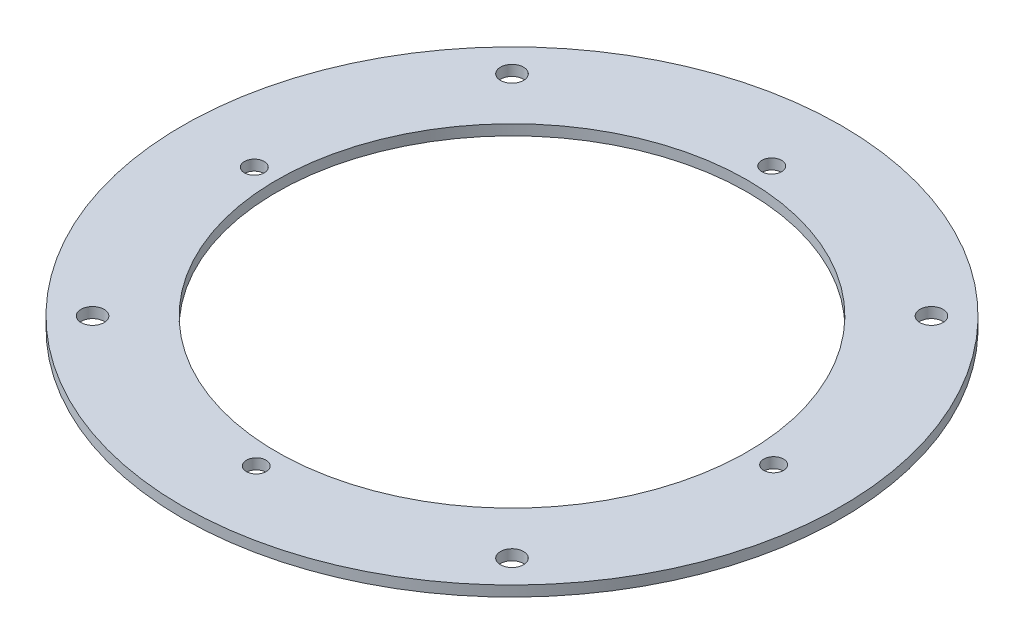
SolidWorks part; units mm, degrees
material "6061 Alloy"
ref_plane "Front Plane" through (0, 0, 0) normal (0, 0, 1) x (1, 0, 0)
ref_plane "Top Plane" through (0, 0, 0) normal (0, 1, 0) x (1, 0, 0)
ref_plane "Right Plane" through (0, 0, 0) normal (1, 0, 0) x (0, 0, -1)
sketch "Sketch1" plane through (0, 0, 0) normal (0, 1, 0) x (1, 0, 0)
  circle A0 centre (0, 0) radius 50
  circle A1 centre (0, 0) radius 35.715
  dimension "D1" = 100
  dimension "D2" = 71.43
extrude "Boss-Extrude1" add sketch "Sketch1" along normal blind 1.59
sketch "Sketch2" plane through (0, 1.59, 0) normal (0, 1, 0) x (1, 0, 0)
  circle A0 centre (0, 0) radius 39.4 construction
  circle A1 centre (0, 39.4) radius 1.5
  circle A2 centre (39.4, 0.3) radius 1.5
  circle A3 centre (0.3, -39.1) radius 1.5
  circle A4 centre (-39.1, 0) radius 1.5
  point P14 (0.15, 0.15)
  dimension "D1" = 78.8
  dimension "D2" = 3
  dimension "D3" = 4
extrude "Cut-Extrude1" cut sketch "Sketch2" against normal blind 2
sketch "Sketch3" plane through (0, 1.59, 0) normal (0, 1, 0) x (1, 0, 0)
  circle A0 centre (0, 0) radius 45 construction
  circle A1 centre (-31.8198, 31.8198) radius 1.75
  circle A2 centre (31.8198, 31.8198) radius 1.75
  circle A3 centre (31.8198, -31.8198) radius 1.75
  circle A4 centre (-31.8198, -31.8198) radius 1.75
  point P14 (0, 0)
  dimension "D1" = 90
  dimension "D3" = 3.5
  dimension "D2" = 31.8198
  dimension "D4" = 4
extrude "Cut-Extrude2" cut sketch "Sketch3" against normal blind 2
